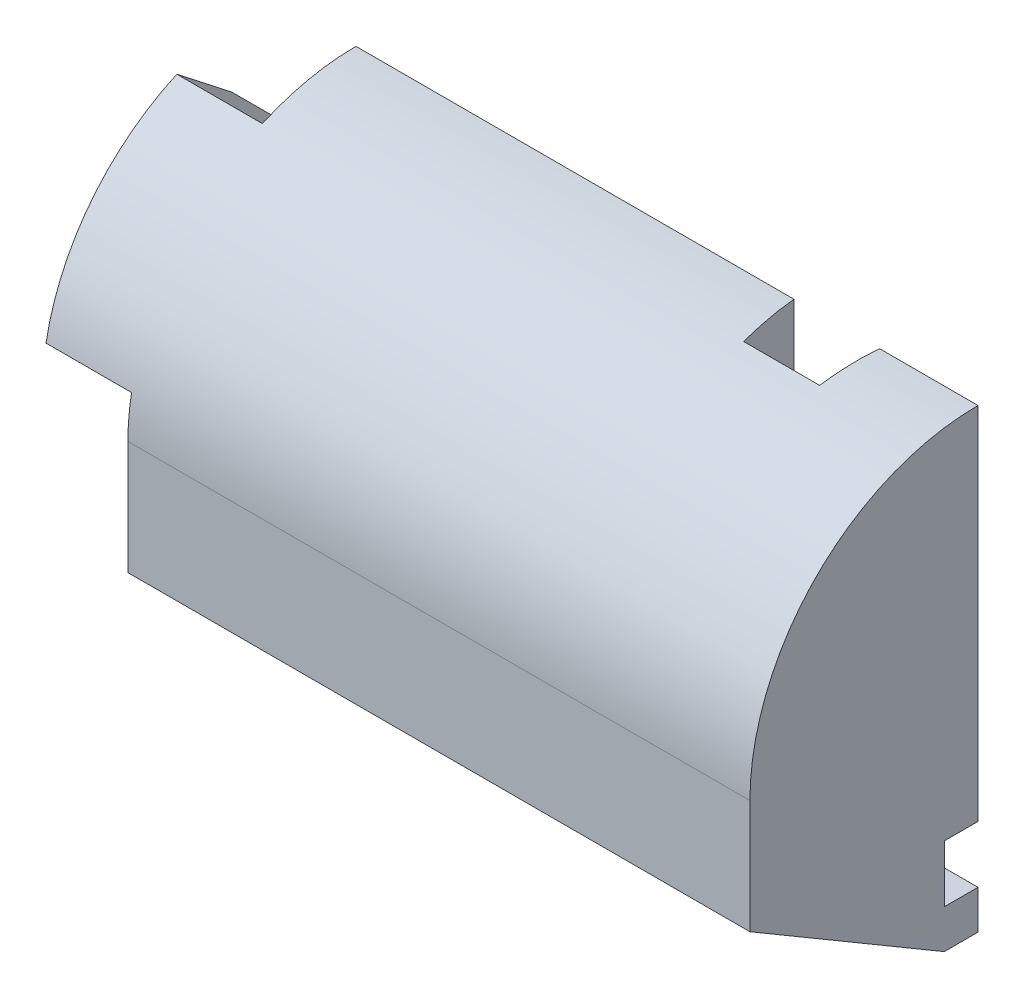
SolidWorks part; units mm, degrees
material "Alliage 1060"
ref_plane "Plan de face" through (0, 0, 0) normal (0, 0, 1) x (1, 0, 0)
ref_plane "Plan de dessus" through (0, 0, 0) normal (0, 1, 0) x (1, 0, 0)
ref_plane "Plan de droite" through (0, 0, 0) normal (1, 0, 0) x (0, 0, -1)
sketch "Esquisse1" plane through (0, 0, 0) normal (1, 0, 0) x (0, 0, -1)
  line L0 (0, 0) -> (0, 88)
  line L1 (0, 94.6) -> (0, -94.6) construction
  line L5 (-13, -88) -> (0, -88)
  line L6 (0, -88) -> (0, 0)
  line L7 (-13, -88) -> (-88, -43.8534)
  line L8 (-88, -43.8534) -> (-88, 0)
  arc A0 (0, 88) -> (-88, 0) centre (0, 0) ccw
  dimension "D1" = 88
  dimension "D2" = 88
  dimension "D3" = 13
  dimension "D4" = 88
extrude "Boss.-Extru.1" add sketch "Esquisse1" along normal blind 240 contours L8 A0 L0 L6 L5 L7
sketch "Esquisse2" plane through (0, 0, 0) normal (1, 0, 0) x (0, 0, -1)
  circle A0 centre (0, 0) radius 28.575
extrude "Enlèv. mat.-Extru.1" cut sketch "Esquisse2" along normal blind 235
sketch "Esquisse3" plane through (0, 0, 0) normal (1, 0, 0) x (0, 0, -1)
  circle A0 centre (0, 0) radius 44.45
extrude "Enlèv. mat.-Extru.2" cut sketch "Esquisse3" along normal blind 78
sketch "Esquisse5" plane through (0, 0, 0) normal (0, 0, 1) x (1, 0, 0)
  line L0 (240, -88) -> (240, -73)
  line L1 (240, -88) -> (240, 88) construction
  line L2 (240, -73) -> (127, -73)
  line L3 (240, -51) -> (240, -73)
  line L4 (127, -51) -> (240, -51)
  arc A0 (127, -73) -> (127, -51) centre (127, -62) cw
  dimension "D1" = 15
  dimension "D2" = 113
  dimension "D4" = 22
extrude "Enlèv. mat.-Extru.4" cut sketch "Esquisse5" along normal blind 13 contours A0 L2 L3 L4
sketch "Esquisse6" plane through (0, 0, 0) normal (1, 0, 0) x (0, 0, -1)
  line L0 (0, 0) -> (-40.1885, 31.3987)
  line L1 (48.4, 0) -> (-48.4, 0) construction
  line L2 (-40.1885, 31.3987) -> (-65.4307, -0.9097)
  line L3 (-14.9464, 63.7072) -> (-40.1885, 31.3987)
  line L4 (-14.9464, 63.7072) -> (-36.1165, 80.2471)
  line L5 (-65.4307, -0.9097) -> (-86.6008, 15.6302)
  line L7 (-36.1165, 80.2471) -> (-14.9464, 63.7072)
  line L8 (-14.9464, 63.7072) -> (-65.4307, -0.9097)
  line L9 (-65.4307, -0.9097) -> (-84.7673, 14.5089)
  arc A0 (0, 88) -> (-88, 0) centre (0, 0) ccw construction
  arc A1 (-86.6008, 15.6302) -> (-36.1165, 80.2471) centre (0, 0) cw
  dimension "D1" = 38
extrude "Boss.-Extru.2" add sketch "Esquisse6" against normal blind 33 contours A1 L9 L2 L3 L4
sketch "Esquisse7" plane through (0, 0, 0) normal (0, 1, 0) x (1, 0, 0)
  line L0 (240, 0) -> (202, 0)
  line L1 (-96.8, 0) -> (96.8, 0) construction
  line L2 (240, -88) -> (240, 0) construction
  line L3 (169, 0) -> (202, 0)
  line L4 (202, -21.2306) -> (169, -21.2306)
  line L6 (202, 0) -> (200.1426, -21.2306)
  line L7 (169, 0) -> (170.8574, -21.2306)
extrude "Enlèv. mat.-Extru.5" cut sketch "Esquisse7" along normal blind 100 contours L3 L7 L4 L6
equation "\"A\" = 240"
equation "\"B\" = 113"
equation "\"C\"= 88"
equation "\"D2@Esquisse1\"=\"C\""
equation "\"D1@Esquisse1\"=\"C\""
equation "\"D4@Esquisse1\"=\"C\""
equation "\"D1@Boss.-Extru.1\"=\"A\""
equation "\"D2@Esquisse5\"=\"B\""
